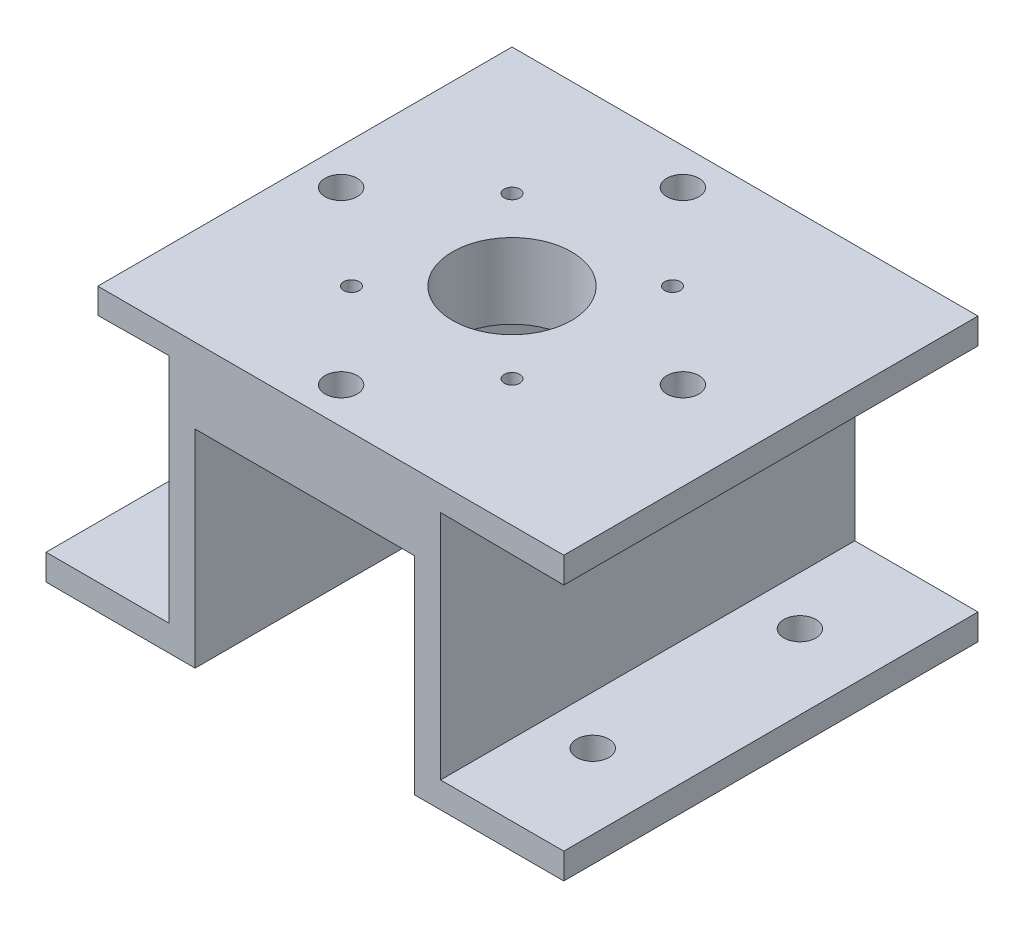
SolidWorks part; units mm, degrees
ref_plane "Front Plane" through (0, 0, 0) normal (0, 0, 1) x (1, 0, 0)
ref_plane "Top Plane" through (0, 0, 0) normal (0, 1, 0) x (1, 0, 0)
ref_plane "Right Plane" through (0, 0, 0) normal (1, 0, 0) x (0, 0, -1)
sketch "Sketch1" plane through (0, 0, 0) normal (0, 0, 1) x (1, 0, 0)
  line L0 (0, 0) -> (21.2, 0)
  line L1 (21.2, 0) -> (21.2, -40)
  line L2 (21.2, -40) -> (50, -40)
  line L4 (-26.15, 14.5) -> (26.15, 14.5)
  line L5 (26.2, 5) -> (26.2, 9.75)
  line L6 (26.2, 5) -> (26.2, -35)
  line L7 (35.7, 14.5) -> (35.7, -25.5) construction
  line L8 (35.7, -25.5) -> (50, -25.5) construction
  line L9 (26.2, -35) -> (50, -35)
  line L10 (0, 5) -> (26.2, 5) construction
  line L11 (50, -35) -> (50, -40)
  line L12 (0, 14.5) -> (35.7, 14.5) construction
  line L13 (26.15, 14.5) -> (50, 14.5)
  line L14 (50, 14.5) -> (50, 9.5)
  line L15 (50, 9.5) -> (26.2, 9.75)
  line L16 (0, 0) -> (0, -69.3084) construction
  line L17 (-50, 9.5) -> (-26.2, 9.75)
  line L18 (-50, 14.5) -> (-50, 9.5)
  line L19 (-26.15, 14.5) -> (-50, 14.5)
  line L20 (-50, -35) -> (-50, -40)
  line L21 (-26.2, -35) -> (-50, -35)
  line L22 (-26.2, 5) -> (-26.2, -35)
  line L23 (-26.2, 5) -> (-26.2, 9.75)
  line L24 (-21.2, -40) -> (-50, -40)
  line L25 (-21.2, 0) -> (-21.2, -40)
  line L26 (0, 0) -> (-21.2, 0)
  dimension "D1" = 21.2
  dimension "D2" = 40
  dimension "D3" = 50
  dimension "D6" = 5
  dimension "D4" = 14.5
  dimension "D5" = 5
extrude "Boss-Extrude3" add sketch "Sketch1" along normal mid plane 80
sketch "Sketch4" plane through (0, 14.5, 0) normal (0, 1, 0) x (1, 0, 0)
  line L5 (-15.5, 15.5) -> (15.5, -15.5) construction
  line L6 (-15.5, -15.5) -> (15.5, 15.5) construction
  circle A0 centre (0, 0) radius 11.5
  circle A1 centre (-15.5, 15.5) radius 1.5
  circle A2 centre (-15.5, -15.5) radius 1.5
  circle A3 centre (15.5, -15.5) radius 1.5
  circle A4 centre (15.5, 15.5) radius 1.5
  dimension "D1" = 23
  dimension "D4" = 3
  dimension "D2" = 31
  dimension "D3" = 31
extrude "Cut-Extrude1" cut sketch "Sketch4" against normal blind 80
sketch "Sketch5" plane through (0, 14.5, 0) normal (0, 1, 0) x (1, 0, 0)
  circle A0 centre (33, 0) radius 3.1
  circle A1 centre (0, -33) radius 3.1
  circle A2 centre (-33, 0) radius 3.1
  circle A3 centre (0, 33) radius 3.1
  point P14 (0, 0)
  dimension "D2" = 6.2
  dimension "D3" = 4
extrude "Cut-Extrude2" cut sketch "Sketch5" against normal blind 40
sketch "Sketch9" plane through (0, -40, 0) normal (0, -1, 0) x (1, 0, 0)
  line L0 (35.6, 40) -> (35.6, -40) construction
  line L1 (21.2, 40) -> (50, 40) construction
  line L2 (21.2, -40) -> (50, -40) construction
  circle A0 centre (35.6, 20) radius 3.1
  circle A1 centre (35.6, -20) radius 3.1
  circle A2 centre (-35.6, -20) radius 3.1
  circle A3 centre (-35.6, 20) radius 3.1
  point P10 (35.6, 0)
  dimension "D1" = 6.2
  dimension "D2" = 6.2
  dimension "D5" = 6.2
  dimension "D6" = 6.2
  dimension "D3" = 20
  dimension "D4" = 20
extrude "Cut-Extrude3" cut sketch "Sketch9" against normal blind 10
sketch "Sketch11" plane through (0, 14.5, 0) normal (0, 1, 0) x (1, 0, 0)
  line L0 (0, 0) -> (0, -40)
  line L1 (50, -40) -> (-50, -40) construction
  line L3 (-40, -40) -> (-40, 40)
  line L4 (50, 40) -> (-50, 40) construction
  line L5 (-40, -40) -> (-50, -40)
  line L6 (-50, -40) -> (-50, 40)
  line L7 (-50, 40) -> (-40, 40)
  point P11 (-40, 0)
  line M15 (50, 40) -> (-50, 40)
  line M16 (-50, 40) -> (-50, -40)
  line M17 (-50, -40) -> (50, -40)
extrude "Cut-Extrude4" cut sketch "Sketch11" against normal blind 10 contours L3 M17 M15 M16
